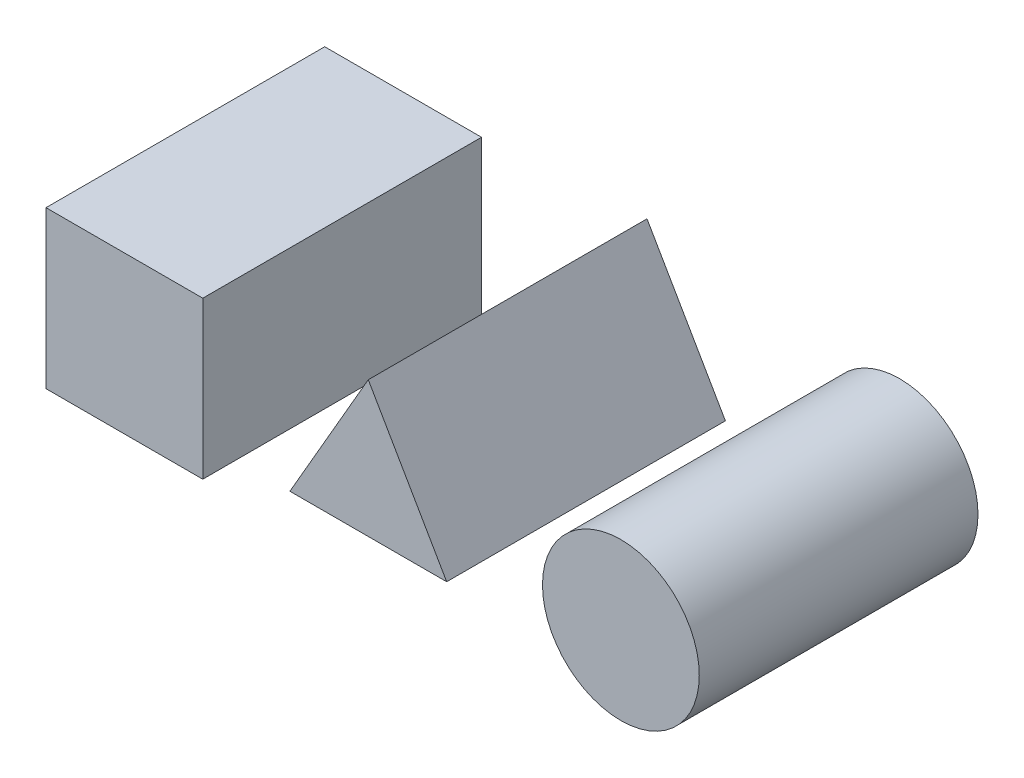
SolidWorks part; units mm, degrees
ref_plane "Front Plane" through (0, 0, 0) normal (0, 0, 1) x (1, 0, 0)
ref_plane "Top Plane" through (0, 0, 0) normal (0, 1, 0) x (1, 0, 0)
ref_plane "Right Plane" through (0, 0, 0) normal (1, 0, 0) x (0, 0, -1)
sketch "Sketch1" plane through (0, 0, 0) normal (0, 0, 1) x (1, 0, 0)
  line L0 (-122.5, 0) -> (122.5, 0) construction
  line L1 (-122.5, 60) -> (122.5, 60)
  line L2 (-122.5, 60) -> (-122.5, -60)
  line L3 (-122.5, -60) -> (122.5, -60)
  line L4 (122.5, 60) -> (122.5, -60)
  line L5 (0, 60) -> (0, -60) construction
  line L6 (-22.5, -12.9904) -> (0, 25.9808)
  line L7 (-92.5, 22.5) -> (-47.5, 22.5)
  line L8 (-92.5, 22.5) -> (-92.5, -22.5)
  line L9 (-92.5, -22.5) -> (-47.5, -22.5)
  line L10 (-47.5, 22.5) -> (-47.5, -22.5)
  line L11 (-92.5, 22.5) -> (-47.5, -22.5) construction
  line L12 (-92.5, -22.5) -> (-47.5, 22.5) construction
  line L14 (-1.3522, 0) -> (0, -1.3522)
  line L18 (0, 25.9808) -> (22.5, -12.9904)
  line L19 (22.5, -12.9904) -> (-22.5, -12.9904)
  line L20 (-22.5, -12.9904) -> (11.25, 6.4952) construction
  line L21 (22.5, -12.9904) -> (-11.25, 6.4952) construction
  line L22 (0, 25.9808) -> (0, 0) construction
  circle A0 centre (72.5, 0) radius 22.5
  point P10 (-70, 0)
  point P20 (0, 0)
  point P27 (7.7505, -5.3087)
  point P28 (0, 0)
  dimension "D2" = 50
  dimension "cylinder" = 45
  dimension "D1" = 30
  dimension "square2" = 45
  dimension "square" = 45
  dimension "triangle3" = 45
  dimension "triangle2" = 45
  dimension "triangle" = 45
extrude "Boss-Extrude1" add sketch "Sketch1" along normal blind 80
